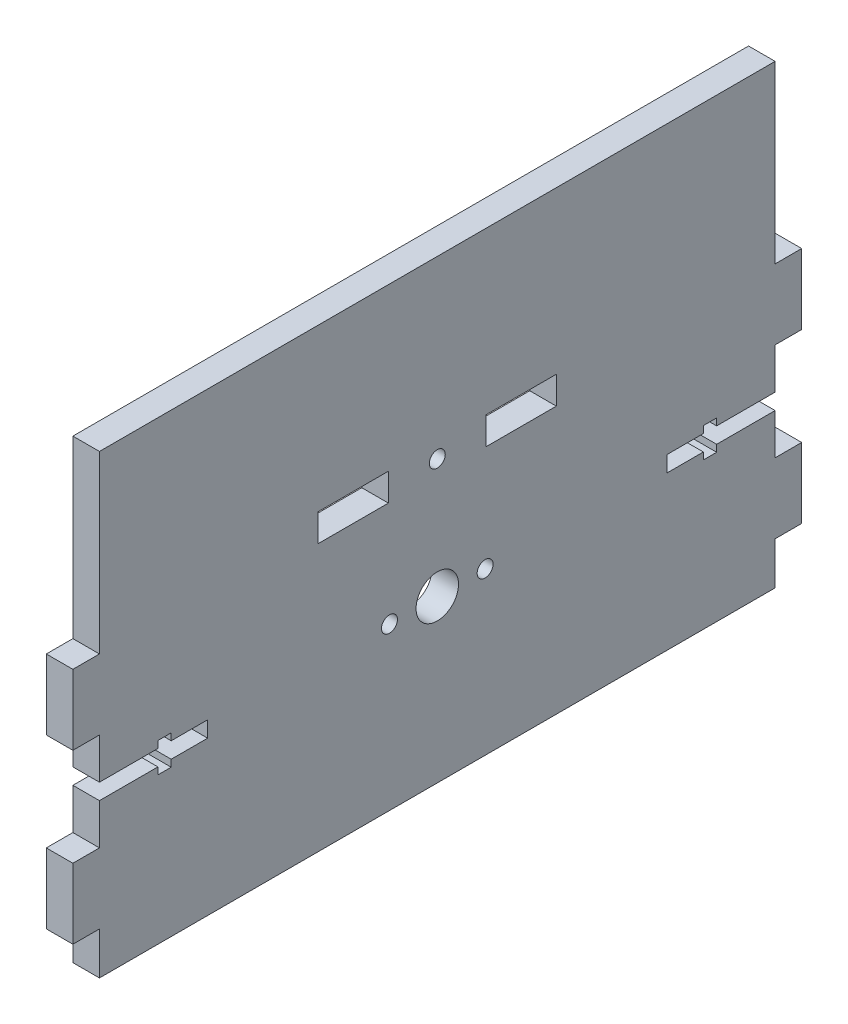
SolidWorks part; units mm, degrees
ref_plane "Front" through (0, 0, 0) normal (0, 0, 1) x (1, 0, 0)
ref_plane "Top" through (0, 0, 0) normal (0, 1, 0) x (1, 0, 0)
ref_plane "Right" through (0, 0, 0) normal (1, 0, 0) x (0, 0, -1)
sketch "Sketch1" plane through (0, 0, 0) normal (1, 0, 0) x (0, 0, -1)
  line L0 (-135.7814, 106.7335) -> (-135.7814, 139.7335)
  line L1 (-135.7814, 139.7335) -> (-8.6514, 139.7335)
  line L2 (-8.6514, 139.7335) -> (-8.6514, 106.7335)
  line L3 (-72.2164, 106.7335) -> (-72.2164, 139.7335) construction
  line L4 (-135.7814, 53.9335) -> (-8.6514, 53.9335)
  line L5 (-115.4241, 84.3335) -> (-72.2164, 84.3335) construction
  line L6 (-135.7814, 61.9335) -> (-135.7814, 53.9335)
  line L7 (-135.7814, 61.9335) -> (-140.7814, 61.9335)
  line L8 (-140.7814, 61.9335) -> (-140.7814, 75.1335)
  line L9 (-140.7814, 93.5335) -> (-140.7814, 106.7335)
  line L10 (-135.7814, 93.5335) -> (-135.7814, 85.8335)
  line L11 (-135.7814, 75.1335) -> (-140.7814, 75.1335)
  line L12 (-115.4241, 82.8335) -> (-115.4241, 85.8335)
  line L13 (-135.7814, 82.8335) -> (-135.7814, 75.1335)
  line L14 (-49.8164, 109.3335) -> (-49.8164, 104.1335)
  line L16 (-3.6514, 93.5335) -> (-3.6514, 106.7335)
  line L17 (-135.7814, 106.7335) -> (-140.7814, 106.7335)
  line L18 (-135.7814, 93.5335) -> (-140.7814, 93.5335)
  line L27 (-49.8164, 104.1335) -> (-63.0164, 104.1335)
  line L28 (-81.4164, 104.1335) -> (-94.6164, 104.1335)
  line L29 (-94.6164, 109.3335) -> (-81.4164, 109.3335)
  line L30 (-63.0164, 109.3335) -> (-63.0164, 104.1335)
  line L31 (-63.0164, 109.3335) -> (-49.8164, 109.3335)
  line L32 (-94.6164, 109.3335) -> (-94.6164, 104.1335)
  line L33 (-81.4164, 109.3335) -> (-81.4164, 104.1335)
  line L34 (-63.0164, 106.7335) -> (-81.4164, 106.7335) construction
  line L35 (-19.6514, 85.8335) -> (-19.6514, 87.1335)
  line L36 (-19.6514, 82.8335) -> (-19.6514, 81.5335)
  line L37 (-29.0086, 82.8335) -> (-22.1514, 82.8335)
  line L38 (-8.6514, 85.8335) -> (-19.6514, 85.8335)
  line L39 (-8.6514, 82.8335) -> (-19.6514, 82.8335)
  line L40 (-122.2814, 85.8335) -> (-115.4241, 85.8335)
  line L41 (-122.2814, 81.5335) -> (-124.7814, 81.5335)
  line L42 (-122.2814, 82.8335) -> (-122.2814, 81.5335)
  line L43 (-122.2814, 87.1335) -> (-122.2814, 85.8335)
  line L44 (-124.7814, 87.1335) -> (-122.2814, 87.1335)
  line L45 (-135.7814, 82.8335) -> (-124.7814, 82.8335)
  line L46 (-135.7814, 85.8335) -> (-124.7814, 85.8335)
  line L47 (-115.4241, 82.8335) -> (-122.2814, 82.8335)
  line L48 (-124.7814, 82.8335) -> (-124.7814, 81.5335)
  line L49 (-124.7814, 85.8335) -> (-124.7814, 87.1335)
  line L50 (-19.6514, 87.1335) -> (-22.1514, 87.1335)
  line L51 (-22.1514, 87.1335) -> (-22.1514, 85.8335)
  line L52 (-22.1514, 82.8335) -> (-22.1514, 81.5335)
  line L53 (-22.1514, 81.5335) -> (-19.6514, 81.5335)
  line L54 (-22.1514, 85.8335) -> (-29.0086, 85.8335)
  line L55 (-8.6514, 93.5335) -> (-3.6514, 93.5335)
  line L56 (-8.6514, 106.7335) -> (-3.6514, 106.7335)
  line L57 (-8.6514, 82.8335) -> (-8.6514, 75.1335)
  line L58 (-29.0086, 82.8335) -> (-29.0086, 85.8335)
  line L59 (-8.6514, 75.1335) -> (-3.6514, 75.1335)
  line L60 (-8.6514, 93.5335) -> (-8.6514, 85.8335)
  line L61 (-3.6514, 61.9335) -> (-3.6514, 75.1335)
  line L62 (-8.6514, 61.9335) -> (-3.6514, 61.9335)
  line L63 (-8.6514, 61.9335) -> (-8.6514, 53.9335)
  circle A0 centre (-72.2164, 84.3335) radius 4
  circle A1 centre (-81.2164, 84.3335) radius 1.5
  circle A2 centre (-63.2164, 84.3335) radius 1.5
  circle A3 centre (-72.2164, 106.7335) radius 1.5
extrude "Boss-Extrude1" add sketch "Sketch1" along normal blind 5
